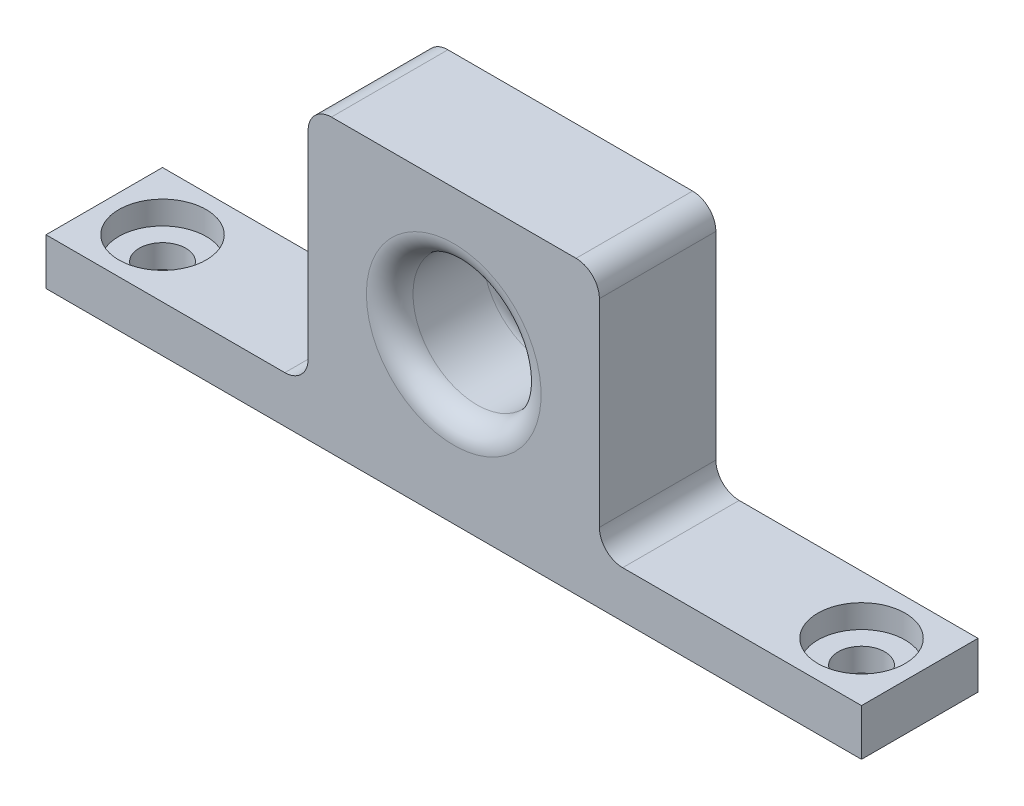
SolidWorks part; units mm, degrees
ref_plane "Front Plane" through (0, 0, 0) normal (0, 0, 1) x (1, 0, 0)
ref_plane "Top Plane" through (0, 0, 0) normal (0, 1, 0) x (1, 0, 0)
ref_plane "Right Plane" through (0, 0, 0) normal (1, 0, 0) x (0, 0, -1)
sketch "Sketch1" plane through (0, 0, 0) normal (0, 1, 0) x (1, 0, 0)
  line L0 (0, 6.35) -> (88.9, 6.35) construction
  line L1 (0, 0) -> (88.9, 0)
  line L2 (0, 0) -> (0, 12.7)
  line L3 (0, 12.7) -> (88.9, 12.7)
  line L4 (88.9, 0) -> (88.9, 12.7)
  line L5 (44.45, 12.7) -> (44.45, 0) construction
  circle A0 centre (6.35, 6.35) radius 2.54
  circle A1 centre (82.55, 6.35) radius 2.54
  dimension "D5" = 5.08
  dimension "D6" = 5.08
  dimension "D1" = 12.7
  dimension "D2" = 88.9
  dimension "D3" = 76.2
  dimension "D4" = 38.1
extrude "Boss-Extrude2" add sketch "Sketch1" along normal blind 5.08
sketch "Sketch3" plane through (0, 5.08, 0) normal (0, 1, 0) x (1, 0, 0)
  circle A0 centre (6.35, 6.35) radius 4.7625
  circle A1 centre (82.55, 6.35) radius 4.7625
  dimension "D1" = 9.525
  dimension "D2" = 9.525
extrude "Cut-Extrude1" cut sketch "Sketch3" against normal blind 2.54
sketch "Sketch4" plane through (0, 0, 0) normal (0, 0, 1) x (1, 0, 0)
  line L0 (0, 0) -> (88.9, 0) construction
  line L1 (28.575, 31.75) -> (60.325, 31.75)
  line L2 (28.575, 31.75) -> (28.575, 0)
  line L3 (28.575, 0) -> (60.325, 0)
  line L4 (60.325, 31.75) -> (60.325, 0)
  line L5 (44.45, 0) -> (44.45, 31.75) construction
  line L6 (0, 5.08) -> (88.9, 5.08) construction
  circle A0 centre (44.45, 16.9545) radius 6.985
  point P10 (0, 0)
  point P11 (0, 0)
  point P12 (0, 0)
  dimension "D2" = 13.97
  dimension "D1" = 31.75
  dimension "D3" = 11.8745
  dimension "D4" = 31.75
extrude "Boss-Extrude3" add sketch "Sketch4" against normal blind 12.7
fillet "Fillet1" radius 2.54 6 edges at (51.435, 16.9545, 0) (51.435, 16.9545, -12.7) (60.325, 5.08, -6.35) (60.325, 31.75, -6.35) (28.575, 31.75, -6.35) (28.575, 5.08, -6.35)
